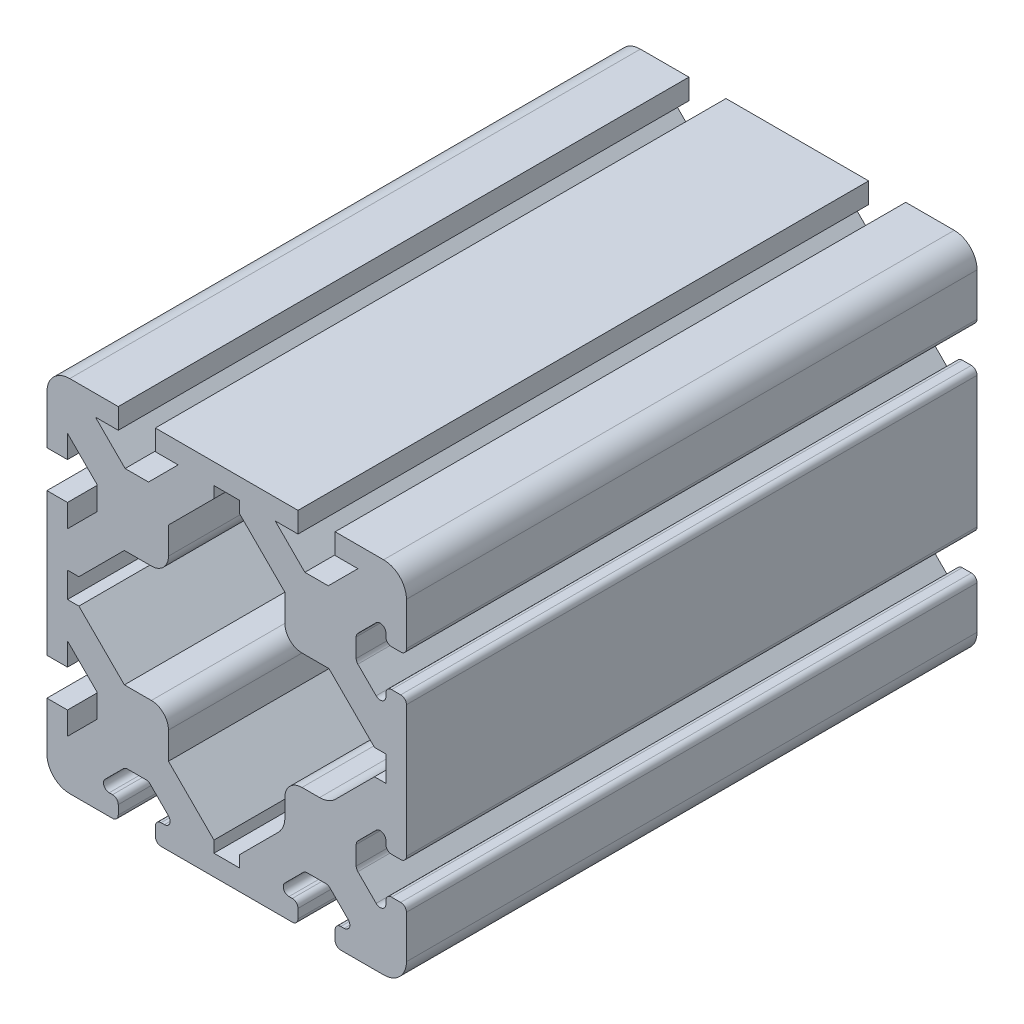
SolidWorks part; units mm, degrees
ref_plane "Front Plane" through (0, 0, 0) normal (0, 0, 1) x (1, 0, 0)
ref_plane "Top Plane" through (0, 0, 0) normal (0, 1, 0) x (1, 0, 0)
ref_plane "Right Plane" through (0, 0, 0) normal (1, 0, 0) x (0, 0, -1)
sketch "Sketch1" plane through (0, 0, 0) normal (0, 0, 1) x (1, 0, 0)
  line L1 (-40.005, -40.005) -> (40.005, -40.005)
  line L2 (-40.005, -40.005) -> (-40.005, 40.005)
  line L3 (-40.005, 40.005) -> (40.005, 40.005)
  line L4 (40.005, -40.005) -> (40.005, 40.005)
  point P4 (0, 0)
  point P5 (0, 0)
  point P6 (0, -40.005)
  point P7 (70.9754, -7.3205)
  point P8 (40.005, 0)
  dimension "D1" = 80.01
extrude "Boss-Extrude1" add sketch "Sketch1" along normal blind 127
fillet "Fillet1" radius 5.08 4 edges at (40.005, 40.005, 63.5) (40.005, -40.005, 63.5) (-40.005, -40.005, 63.5) (-40.005, 40.005, 63.5)
sketch "Sketch2" plane through (0, 0, 127) normal (0, 0, 1) x (1, 0, 0)
  line L0 (24.13, -40.005) -> (24.13, -35.433)
  line L1 (-34.925, -40.005) -> (34.925, -40.005) construction
  line L2 (24.13, -35.433) -> (29.21, -35.433)
  line L3 (29.21, -35.433) -> (22.606, -28.829)
  line L4 (22.606, -28.829) -> (17.399, -28.829)
  line L5 (17.399, -28.829) -> (10.795, -35.433)
  line L6 (10.795, -35.433) -> (15.875, -35.433)
  line L7 (15.875, -40.005) -> (24.13, -40.005)
  line L8 (15.875, -40.005) -> (15.875, -35.433)
  line L9 (40.005, -34.925) -> (40.005, 34.925) construction
  point P12 (20.0025, -40.005)
  point P13 (20.0025, -28.829)
  point P14 (63.0134, 12.7321)
  point P15 (51.972, 11.43)
  dimension "D1" = 8.255
  dimension "D2" = 15.875
  dimension "D3" = 11.176
  dimension "D4" = 4.572
  dimension "D5" = 5.08
extrude "Cut-Extrude1" cut sketch "Sketch2" against normal through all
sketch "Sketch3" plane through (0, 0, 127) normal (0, 0, 1) x (1, 0, 0)
  line L0 (0, 40.005) -> (0, -40.005) construction
  line L1 (34.925, 40.005) -> (-34.925, 40.005) construction
  line L2 (-34.925, -40.005) -> (15.875, -40.005) construction
  line L3 (40.005, 0) -> (-40.005, 0) construction
  line L4 (40.005, -34.925) -> (40.005, 34.925) construction
  line L5 (-40.005, 34.925) -> (-40.005, -34.925) construction
  line L6 (0, 0) -> (38.5171, -38.5171) construction
  line L7 (0, 0) -> (38.5171, 38.5171) construction
  arc A0 (34.925, -40.005) -> (40.005, -34.925) centre (34.925, -34.925) ccw construction
  arc A1 (40.005, 34.925) -> (34.925, 40.005) centre (34.925, 34.925) ccw construction
ref_plane "Plane1" through (0, 0, 0) normal (0.7071, 0.7071, 0) x (0.7071, -0.7071, 0)
mirror "Mirror1" about plane through (0, 0, 0) normal (1, 0, 0) of "Cut-Extrude1"
mirror "Mirror2" about plane through (0, 0, 0) normal (0, 1, 0) of "Mirror1", "Cut-Extrude1"
mirror "Mirror3" about plane through (0, 0, 0) normal (0.7071, 0.7071, 0) of "Mirror2", "Cut-Extrude1", "Mirror1"
fillet "Fillet2" radius 1.27 32 edges at (24.13, -40.005, 63.5) (24.13, -35.433, 63.5) (29.21, -35.433, 63.5) (22.606, -28.829, 63.5) (17.399, -28.829, 63.5) (10.795, -35.433, 63.5) (15.875, -35.433, 63.5) (15.875, -40.005, 63.5) (28.829, 17.399, 63.5) (28.829, 22.606, 63.5) (35.433, 10.795, 63.5) (35.433, 29.21, 63.5) (35.433, 24.13, 63.5) (40.005, 24.13, 63.5) (35.433, 15.875, 63.5) (40.005, 15.875, 63.5) (35.433, -10.795, 63.5) (28.829, -17.399, 63.5) (28.829, -22.606, 63.5) (35.433, -29.21, 63.5) (35.433, -24.13, 63.5) (35.433, -15.875, 63.5) (40.005, -15.875, 63.5) (40.005, -24.13, 63.5) (-29.21, -35.433, 63.5) (-17.399, -28.829, 63.5) (-10.795, -35.433, 63.5) (-22.606, -28.829, 63.5) (-24.13, -35.433, 63.5) (-24.13, -40.005, 63.5) (-15.875, -35.433, 63.5) (-15.875, -40.005, 63.5)
sketch "Sketch5" plane through (0, 0, 127) normal (0, 0, 1) x (1, 0, 0)
  line L0 (2.832, -32.893) -> (12.954, -22.771)
  line L1 (12.954, -22.771) -> (12.954, -12.954)
  line L2 (12.954, -12.954) -> (22.771, -12.954)
  line L3 (22.771, -12.954) -> (32.893, -2.832)
  line L4 (2.832, -32.893) -> (2.832, -35.433)
  line L5 (2.832, -35.433) -> (0, -35.433)
  line L6 (0, -35.433) -> (0, 0)
  line L7 (0, 0) -> (38.5171, -38.5171) construction
  line L8 (29.201, -17.027) -> (33.265, -12.963) construction
  line L9 (40.005, -14.605) -> (40.005, 14.605) construction
  line L10 (0, 0) -> (35.433, 0)
  line L11 (35.433, 0) -> (35.433, -2.832)
  line L12 (35.433, -2.832) -> (32.893, -2.832)
  line L13 (13.8611, -35.433) -> (14.605, -35.433) construction
  arc A0 (34.925, -40.005) -> (40.005, -34.925) centre (34.925, -34.925) ccw construction
  point P2 (38.1949, -3.4499)
  point P14 (38.5171, -38.5171)
  point P19 (5.0149, -30.7101)
  point P24 (0, 0)
  dimension "D1" = 29.21
  dimension "D2" = 27.051
  dimension "D3" = 2.54
extrude "Cut-Extrude2" cut sketch "Sketch5" against normal through all
mirror "Mirror4" about plane through (0, 0, 0) normal (0, 1, 0) of "Cut-Extrude2"
mirror "Mirror5" about plane through (0, 0, 0) normal (1, 0, 0) of "Mirror4", "Cut-Extrude2"
fillet "Fillet3" radius 3.81 4 edges at (-12.954, -12.954, 63.5) (-12.954, 12.954, 63.5) (12.954, 12.954, 63.5) (12.954, -12.954, 63.5)
fillet "Fillet4" radius 5.08 2 edges at (22.771, -12.954, 63.5) (12.954, -22.771, 63.5)
